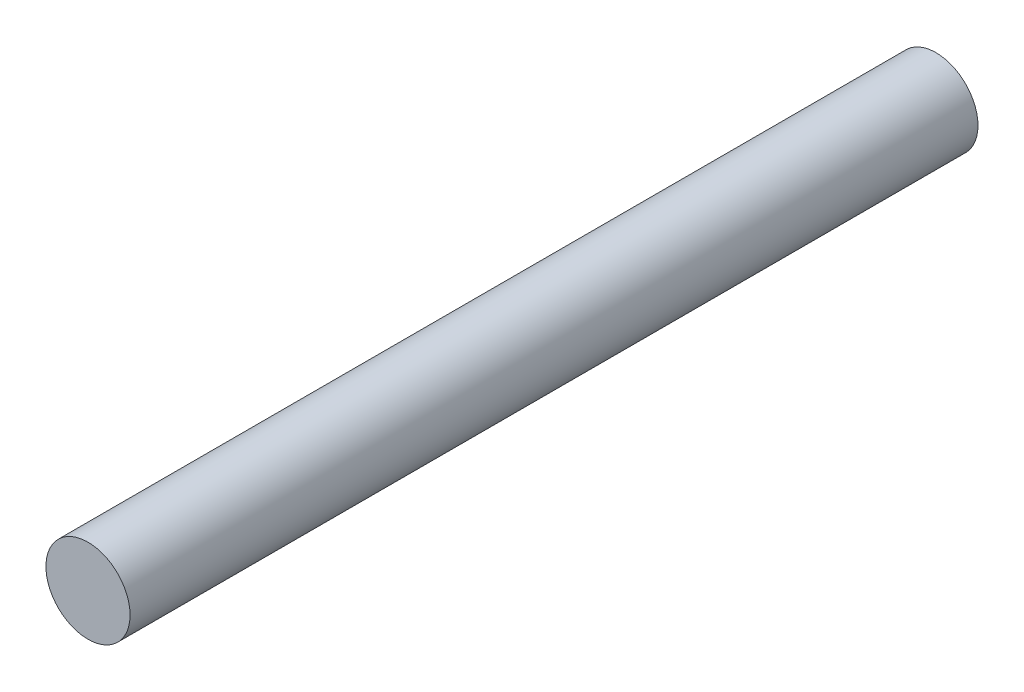
SolidWorks part; units mm, degrees
ref_plane "Front Plane" through (0, 0, 0) normal (0, 0, 1) x (1, 0, 0)
ref_plane "Top Plane" through (0, 0, 0) normal (0, 1, 0) x (1, 0, 0)
ref_plane "Right Plane" through (0, 0, 0) normal (1, 0, 0) x (0, 0, -1)
sketch "Sketch1" plane through (0, 0, 0) normal (0, 0, 1) x (1, 0, 0)
  circle A0 centre (20, 20) radius 3.9688
extrude "Boss-Extrude1" add sketch "Sketch1" along normal blind 80
